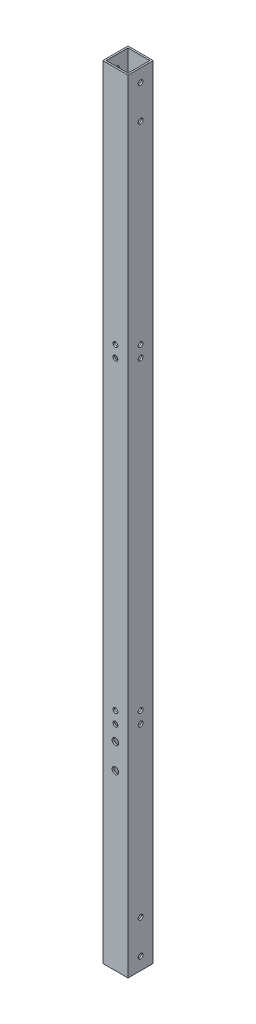
SolidWorks part; units mm, degrees
material "Thornel Mat VMA"
ref_plane "前视基准面" through (0, 0, 0) normal (0, 0, 1) x (1, 0, 0)
ref_plane "上视基准面" through (0, 0, 0) normal (0, 1, 0) x (1, 0, 0)
ref_plane "右视基准面" through (0, 0, 0) normal (1, 0, 0) x (0, 0, -1)
sketch "草图1" plane through (0, 0, 0) normal (0, 1, 0) x (1, 0, 0)
  line L1 (-7.5, -7.5) -> (7.5, -7.5)
  line L2 (-7.5, -7.5) -> (-7.5, 7.5)
  line L3 (-7.5, 7.5) -> (7.5, 7.5)
  line L4 (7.5, -7.5) -> (7.5, 7.5)
  line L5 (-7.5, -7.5) -> (7.5, 7.5) construction
  line L6 (-7.5, 7.5) -> (7.5, -7.5) construction
  point P0 (0, 0)
  dimension "D1" = 15
  dimension "D2" = 15
extrude "拉伸-薄壁1" add sketch "草图1" along normal blind 465 thin thin type one direction reverse wall 1
sketch "草图2" plane through (0, 0, 7.5) normal (0, 0, 1) x (1, 0, 0)
  line L0 (0, 0) -> (0, 465) construction
  line L1 (-7.5, 465) -> (7.5, 465) construction
  line L2 (-7.5, 0) -> (7.5, 0) construction
  circle A0 centre (0, 7.5) radius 1.45 construction
  circle A1 centre (0, 27.5) radius 1.45 construction
  circle A2 centre (0, 118) radius 1.95
  circle A3 centre (0, 103) radius 1.95
  circle A4 centre (0, 134) radius 1.45
  circle A5 centre (0, 127) radius 1.45
  circle A6 centre (0, 322.5) radius 1.45
  circle A7 centre (0, 315.5) radius 1.45
  dimension "D1" = 2.9
  dimension "D4" = 3.9
  dimension "D5" = 118
  dimension "D6" = 15
  dimension "D8" = 7
  dimension "D9" = 134
  dimension "D10" = 181.5
  dimension "D11" = 2.9
  dimension "D2" = 7.5
  dimension "D3" = 20
  dimension "D7" = 7
extrude "切除-拉伸1" cut sketch "草图2" against normal through all
sketch "草图3" plane through (7.5, 0, 0) normal (1, 0, 0) x (0, 0, -1)
  line L0 (0, 0) -> (0, 465) construction
  line L1 (-7.5, 465) -> (7.5, 465) construction
  line L2 (-7.5, 0) -> (7.5, 0) construction
  circle A0 centre (0, 457.5) radius 1.45
  circle A1 centre (0, 437.5) radius 1.45
  circle A2 centre (0, 134) radius 1.45
  circle A3 centre (0, 127) radius 1.45
  circle A4 centre (0, 315.5) radius 1.45
  circle A5 centre (0, 322.5) radius 1.45
  circle A6 centre (0, 7.5) radius 1.45
  circle A7 centre (0, 27.5) radius 1.45
  dimension "D1" = 2.9
  dimension "D2" = 7.5
  dimension "D3" = 20
  dimension "D5" = 7
  dimension "D6" = 181.5
  dimension "D7" = 7
  dimension "D8" = 7.5
  dimension "D9" = 20
  dimension "D4" = 134
extrude "切除-拉伸2" cut sketch "草图3" against normal through all
